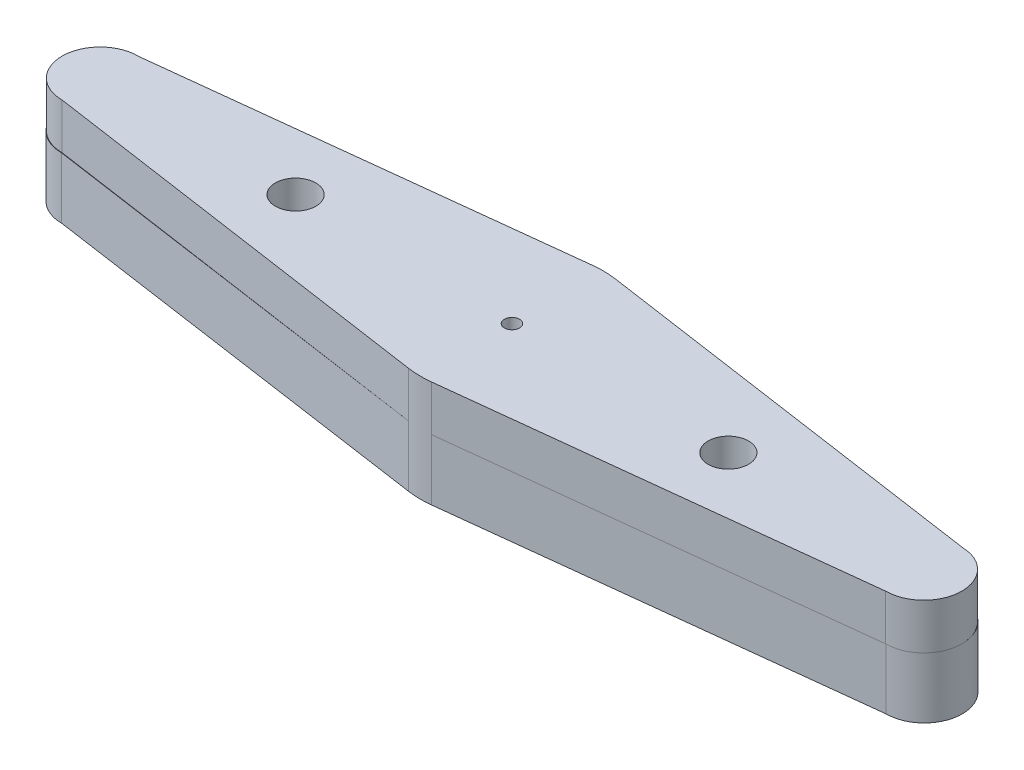
SolidWorks part; units mm, degrees
ref_plane "Front Plane" through (0, 0, 0) normal (0, 0, 1) x (1, 0, 0)
ref_plane "Top Plane" through (0, 0, 0) normal (0, 1, 0) x (1, 0, 0)
ref_plane "Right Plane" through (0, 0, 0) normal (1, 0, 0) x (0, 0, -1)
sketch "Sketch1" plane through (0, 0, 0) normal (0, 1, 0) x (1, 0, 0)
  line L0 (27.5, -0.4176) -> (-27.5, 0.4176) construction
  line L1 (27.5759, 2.0812) -> (0.8573, 5.9384)
  line L2 (-27.4241, 2.9165) -> (-0.6787, 5.9615)
  line L3 (-27.5, -2.0824) -> (-0.8594, -5.9381)
  line L4 (27.5, -2.9176) -> (0.6766, -5.9617)
  line L5 (17, -0.2582) -> (-17, 0.2582) construction
  line L6 (-17, 2.2582) -> (0, 3.75)
  line L7 (0, 3.75) -> (17, 1.7418)
  line L8 (-17, -1.7418) -> (0, -3.75)
  line L9 (0, -3.75) -> (17, -2.2582)
  arc A0 (-0.8738, -3.6468) -> (0.6531, -3.6927) centre (0, 0) ccw
  arc A1 (-0.8594, -5.9381) -> (0.6766, -5.9617) centre (0, 0) ccw
  arc A2 (-27.4241, 2.9165) -> (-27.5, -2.0824) centre (-27.5, 0.4176) ccw
  arc A3 (27.5, -2.9176) -> (27.5759, 2.0812) centre (27.5, -0.4176) ccw
  arc A4 (0.8573, 5.9384) -> (-0.6787, 5.9615) centre (0, 0) ccw
  arc A5 (-17, 2.2582) -> (-17, -1.7418) centre (-17, 0.2582) ccw
  arc A6 (17, -2.2582) -> (17, 1.7418) centre (17, -0.2582) ccw
  arc A7 (0.8738, 3.6468) -> (-0.6531, 3.6927) centre (0, 0) ccw
  point P7 (0, 0)
  point P17 (0, 0)
  dimension "D2" = 5
  dimension "D3" = 7.5
  dimension "D4" = 12
  dimension "D5" = 4
  dimension "D6" = 34
  dimension "D7" = 17
  dimension "D1" = 55
extrude "Boss-Extrude2" add sketch "Sketch1" along normal blind 4 contours L1 A4 L2 A2 L3 A1 L4 A3 A7 L7 A6 L9 A0 L8 A5 L6
sketch "Sketch2" plane through (0, 4, 0) normal (0, 1, 0) x (1, 0, 0)
  line L0 (27.5, -0.4455) -> (-27.5, 0.4455) construction
  line L1 (27.581, 2.0532) -> (0.8632, 5.9376)
  line L2 (-27.419, 2.9442) -> (-0.6728, 5.9622)
  line L3 (-27.5, -2.0545) -> (-0.8655, -5.9372)
  line L4 (27.5, -2.9455) -> (0.6705, -5.9624)
  line L5 (15, -0.243) -> (-15, 0.243) construction
  circle A0 centre (0, 0) radius 0.5
  arc A1 (-0.8655, -5.9372) -> (0.6705, -5.9624) centre (0, 0) ccw
  arc A2 (-27.419, 2.9442) -> (-27.5, -2.0545) centre (-27.5, 0.4455) ccw
  arc A3 (27.5, -2.9455) -> (27.581, 2.0532) centre (27.5, -0.4455) ccw
  arc A4 (0.8632, 5.9376) -> (-0.6728, 5.9622) centre (0, 0) ccw
  circle A8 centre (-14.45, 0.2341) radius 1.33
  circle A9 centre (14.45, -0.2341) radius 1.33
  point P6 (0, 0)
  point P16 (0, 0)
  dimension "D2" = 5
  dimension "D3" = 1
  dimension "D4" = 12
  dimension "D5" = 14.45
  dimension "D6" = 2.66
  dimension "D1" = 55
  dimension "D7" = 14.45
extrude "Boss-Extrude5" add sketch "Sketch2" along normal blind 3
